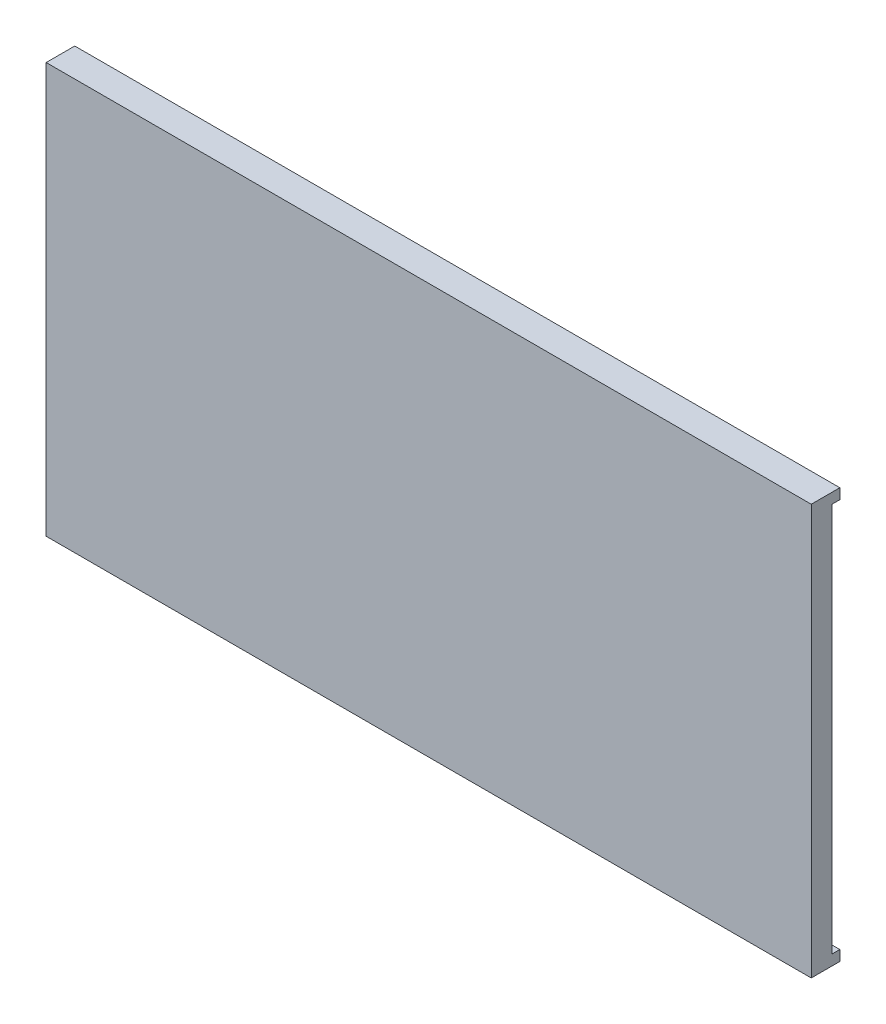
SolidWorks part; units mm, degrees
ref_plane "前视基准面" through (0, 0, 0) normal (0, 0, 1) x (1, 0, 0)
ref_plane "上视基准面" through (0, 0, 0) normal (0, 1, 0) x (1, 0, 0)
ref_plane "右视基准面" through (0, 0, 0) normal (1, 0, 0) x (0, 0, -1)
other "Configuration Table"
sketch "草图2" plane through (0, 0, 0) normal (0, 0, 1) x (1, 0, 0)
  line L0 (-39.878, -84.328) -> (276.733, -84.328) construction
  line L1 (-39.878, 65.151) -> (250.122, 65.151) construction
  line L2 (-39.878, 65.151) -> (-39.878, -84.328) construction
  line L3 (-39.878, -84.328) -> (250.122, -84.328) construction
  line L4 (250.122, 65.151) -> (250.122, -84.328) construction
  line L5 (-40.078, 65.351) -> (-40.078, -84.528)
  line L6 (-40.078, -84.528) -> (250.322, -84.528)
  line L7 (250.322, 65.351) -> (250.322, -84.528)
  line L8 (-40.078, 65.351) -> (250.322, 65.351)
  dimension "D1" = 290
  dimension "D2" = 0.2
sketch "草图3" plane through (0, 0, 0) normal (0, 0, 1) x (1, 0, 0)
  line L0 (250.322, 65.351) -> (250.322, -84.528) construction
  line L1 (-40.078, -84.528) -> (250.322, -84.528) construction
  line L2 (-40.078, 65.351) -> (-40.078, -84.528) construction
  line L3 (-40.078, 65.351) -> (250.322, 65.351) construction
  line L4 (250.322, 65.351) -> (250.322, -84.528) construction
  line L5 (-40.078, -84.528) -> (250.322, -84.528) construction
  line L6 (-40.078, 65.351) -> (-40.078, -84.528) construction
  line L7 (-40.078, 65.351) -> (250.322, 65.351) construction
  line L9 (250.322, 69.351) -> (-44.078, 69.351)
  line L10 (250.322, 69.351) -> (250.322, -88.528)
  line L11 (250.322, -88.528) -> (-44.078, -88.528)
  line L12 (-44.078, 69.351) -> (-44.078, -88.528)
  dimension "D1" = 4
  dimension "D2" = 4
  dimension "D3" = 4
sketch "草图5" plane through (0, 0, 0) normal (0, 0, 1) x (1, 0, 0)
  circle A0 centre (-27.455, -57.53) radius 8.25 construction
  circle A1 centre (-2.38, -57.53) radius 8.25 construction
  circle A2 centre (21.43, -57.53) radius 8.25 construction
  circle A3 centre (92.87, -57.53) radius 8.25 construction
  circle A4 centre (185.74, -38.1) radius 8.25 construction
  circle A5 centre (166.69, -38.1) radius 8.25 construction
  circle A6 centre (147.64, -38.1) radius 8.25 construction
  circle A7 centre (128.59, -38.1) radius 8.25 construction
  circle A8 centre (109.54, -38.1) radius 8.25 construction
  circle A9 centre (90.49, -38.1) radius 8.25 construction
  circle A10 centre (71.44, -38.1) radius 8.25 construction
  circle A11 centre (52.39, -38.1) radius 8.25 construction
  circle A12 centre (33.34, -38.1) radius 8.25 construction
  circle A13 centre (14.29, -38.1) radius 8.25 construction
  circle A14 centre (-16.73, -38.1) radius 8.25 construction
  circle A15 centre (61.91, -19.05) radius 8.25 construction
  circle A16 centre (42.86, -19.05) radius 8.25 construction
  circle A17 centre (23.81, -19.05) radius 8.25 construction
  circle A18 centre (80.96, -19.05) radius 8.25 construction
  circle A19 centre (100.01, -19.05) radius 8.25 construction
  circle A20 centre (119.06, -19.05) radius 8.25 construction
  circle A21 centre (138.11, -19.05) radius 8.25 construction
  circle A22 centre (157.16, -19.05) radius 8.25 construction
  circle A23 centre (176.21, -19.05) radius 8.25 construction
  circle A24 centre (195.26, -19.05) radius 8.25 construction
  circle A25 centre (226.28, -19.05) radius 8.25 construction
  circle A26 centre (4.76, -19.05) radius 8.25 construction
  circle A27 centre (-21.495, -19.05) radius 8.25 construction
  circle A28 centre (171.45, 0) radius 8.25 construction
  circle A29 centre (152.4, 0) radius 8.25 construction
  circle A30 centre (133.35, 0) radius 8.25 construction
  circle A31 centre (114.3, 0) radius 8.25 construction
  circle A32 centre (95.25, 0) radius 8.25 construction
  circle A33 centre (76.2, 0) radius 8.25 construction
  circle A34 centre (57.15, 0) radius 8.25 construction
  circle A35 centre (38.1, 0) radius 8.25 construction
  circle A36 centre (19.05, 0) radius 8.25 construction
  circle A37 centre (0, 0) radius 8.25 construction
  circle A38 centre (228.66, 19.55) radius 8.25 construction
  circle A39 centre (180.98, 19.55) radius 8.25 construction
  circle A40 centre (161.93, 19.55) radius 8.25 construction
  circle A41 centre (142.88, 19.55) radius 8.25 construction
  circle A42 centre (123.83, 19.55) radius 8.25 construction
  circle A43 centre (104.78, 19.55) radius 8.25 construction
  circle A44 centre (85.73, 19.55) radius 8.25 construction
  circle A45 centre (66.68, 19.55) radius 8.25 construction
  circle A46 centre (47.63, 19.55) radius 8.25 construction
  circle A47 centre (28.58, 19.55) radius 8.25 construction
  circle A48 centre (9.53, 19.55) radius 8.25 construction
  circle A49 centre (-9.52, 19.55) radius 8.25 construction
  circle A50 centre (-28.645, 19.55) radius 8.25 construction
  circle A51 centre (-27.455, -57.53) radius 8.25 construction
  circle A52 centre (-2.38, -57.53) radius 8.25 construction
  circle A53 centre (21.43, -57.53) radius 8.25 construction
  circle A54 centre (92.87, -57.53) radius 8.25 construction
  circle A55 centre (185.74, -38.1) radius 8.25 construction
  circle A56 centre (166.69, -38.1) radius 8.25 construction
  circle A57 centre (147.64, -38.1) radius 8.25 construction
  circle A58 centre (128.59, -38.1) radius 8.25 construction
  circle A59 centre (109.54, -38.1) radius 8.25 construction
  circle A60 centre (90.49, -38.1) radius 8.25 construction
  circle A61 centre (71.44, -38.1) radius 8.25 construction
  circle A62 centre (52.39, -38.1) radius 8.25 construction
  circle A63 centre (33.34, -38.1) radius 8.25 construction
  circle A64 centre (14.29, -38.1) radius 8.25 construction
  circle A65 centre (-16.73, -38.1) radius 8.25 construction
  circle A66 centre (61.91, -19.05) radius 8.25 construction
  circle A67 centre (42.86, -19.05) radius 8.25 construction
  circle A68 centre (23.81, -19.05) radius 8.25 construction
  circle A69 centre (80.96, -19.05) radius 8.25 construction
  circle A70 centre (100.01, -19.05) radius 8.25 construction
  circle A71 centre (119.06, -19.05) radius 8.25 construction
  circle A72 centre (138.11, -19.05) radius 8.25 construction
  circle A73 centre (157.16, -19.05) radius 8.25 construction
  circle A74 centre (176.21, -19.05) radius 8.25 construction
  circle A75 centre (195.26, -19.05) radius 8.25 construction
  circle A76 centre (226.28, -19.05) radius 8.25 construction
  circle A77 centre (4.76, -19.05) radius 8.25 construction
  circle A78 centre (-21.495, -19.05) radius 8.25 construction
  circle A79 centre (171.45, 0) radius 8.25 construction
  circle A80 centre (152.4, 0) radius 8.25 construction
  circle A81 centre (133.35, 0) radius 8.25 construction
  circle A82 centre (114.3, 0) radius 8.25 construction
  circle A83 centre (95.25, 0) radius 8.25 construction
  circle A84 centre (76.2, 0) radius 8.25 construction
  circle A85 centre (57.15, 0) radius 8.25 construction
  circle A86 centre (38.1, 0) radius 8.25 construction
  circle A87 centre (19.05, 0) radius 8.25 construction
  circle A88 centre (0, 0) radius 8.25 construction
  circle A89 centre (228.66, 19.55) radius 8.25 construction
  circle A90 centre (180.98, 19.55) radius 8.25 construction
  circle A91 centre (161.93, 19.55) radius 8.25 construction
  circle A92 centre (142.88, 19.55) radius 8.25 construction
  circle A93 centre (123.83, 19.55) radius 8.25 construction
  circle A94 centre (104.78, 19.55) radius 8.25 construction
  circle A95 centre (85.73, 19.55) radius 8.25 construction
  circle A96 centre (66.68, 19.55) radius 8.25 construction
  circle A97 centre (47.63, 19.55) radius 8.25 construction
  circle A98 centre (28.58, 19.55) radius 8.25 construction
  circle A99 centre (9.53, 19.55) radius 8.25 construction
  circle A100 centre (-9.52, 19.55) radius 8.25 construction
  circle A101 centre (-28.645, 19.55) radius 8.25 construction
  circle A102 centre (-28.645, 19.55) radius 8.15
  circle A103 centre (-9.52, 19.55) radius 8.15
  circle A104 centre (9.53, 19.55) radius 8.15
  circle A105 centre (28.58, 19.55) radius 8.15
  circle A106 centre (47.63, 19.55) radius 8.15
  circle A107 centre (66.68, 19.55) radius 8.15
  circle A108 centre (85.73, 19.55) radius 8.15
  circle A109 centre (104.78, 19.55) radius 8.15
  circle A110 centre (123.83, 19.55) radius 8.15
  circle A111 centre (142.88, 19.55) radius 8.15
  circle A112 centre (161.93, 19.55) radius 8.15
  circle A113 centre (180.98, 19.55) radius 8.15
  circle A114 centre (228.66, 19.55) radius 8.15
  circle A115 centre (171.45, 0) radius 8.15
  circle A116 centre (152.4, 0) radius 8.15
  circle A117 centre (133.35, 0) radius 8.15
  circle A118 centre (114.3, 0) radius 8.15
  circle A119 centre (95.25, 0) radius 8.15
  circle A120 centre (76.2, 0) radius 8.15
  circle A121 centre (57.15, 0) radius 8.15
  circle A122 centre (38.1, 0) radius 8.15
  circle A123 centre (19.05, 0) radius 8.15
  circle A124 centre (0, 0) radius 8.15
  circle A125 centre (-21.495, -19.05) radius 8.15
  circle A126 centre (4.76, -19.05) radius 8.15
  circle A127 centre (23.81, -19.05) radius 8.15
  circle A128 centre (42.86, -19.05) radius 8.15
  circle A129 centre (61.91, -19.05) radius 8.15
  circle A130 centre (80.96, -19.05) radius 8.15
  circle A131 centre (100.01, -19.05) radius 8.15
  circle A132 centre (119.06, -19.05) radius 8.15
  circle A133 centre (138.11, -19.05) radius 8.15
  circle A134 centre (157.16, -19.05) radius 8.15
  circle A135 centre (176.21, -19.05) radius 8.15
  circle A136 centre (195.26, -19.05) radius 8.15
  circle A137 centre (226.28, -19.05) radius 8.15
  circle A138 centre (185.74, -38.1) radius 8.15
  circle A139 centre (166.69, -38.1) radius 8.15
  circle A140 centre (147.64, -38.1) radius 8.15
  circle A141 centre (128.59, -38.1) radius 8.15
  circle A142 centre (109.54, -38.1) radius 8.15
  circle A143 centre (90.49, -38.1) radius 8.15
  circle A144 centre (71.44, -38.1) radius 8.15
  circle A145 centre (52.39, -38.1) radius 8.15
  circle A146 centre (33.34, -38.1) radius 8.15
  circle A147 centre (14.29, -38.1) radius 8.15
  circle A148 centre (-16.73, -38.1) radius 8.15
  circle A149 centre (-27.455, -57.53) radius 8.15
  circle A150 centre (-2.38, -57.53) radius 8.15
  circle A151 centre (21.43, -57.53) radius 8.15
  circle A152 centre (92.87, -57.53) radius 8.15
  dimension "D1" = 0.1
extrude "凸台-拉伸2" add sketch "草图3" along normal blind 8 and the other way blind 3
extrude "切除-拉伸2" cut sketch "草图2" against normal blind 3
extrude "切除-拉伸3" cut sketch "草图5" along normal blind 7
